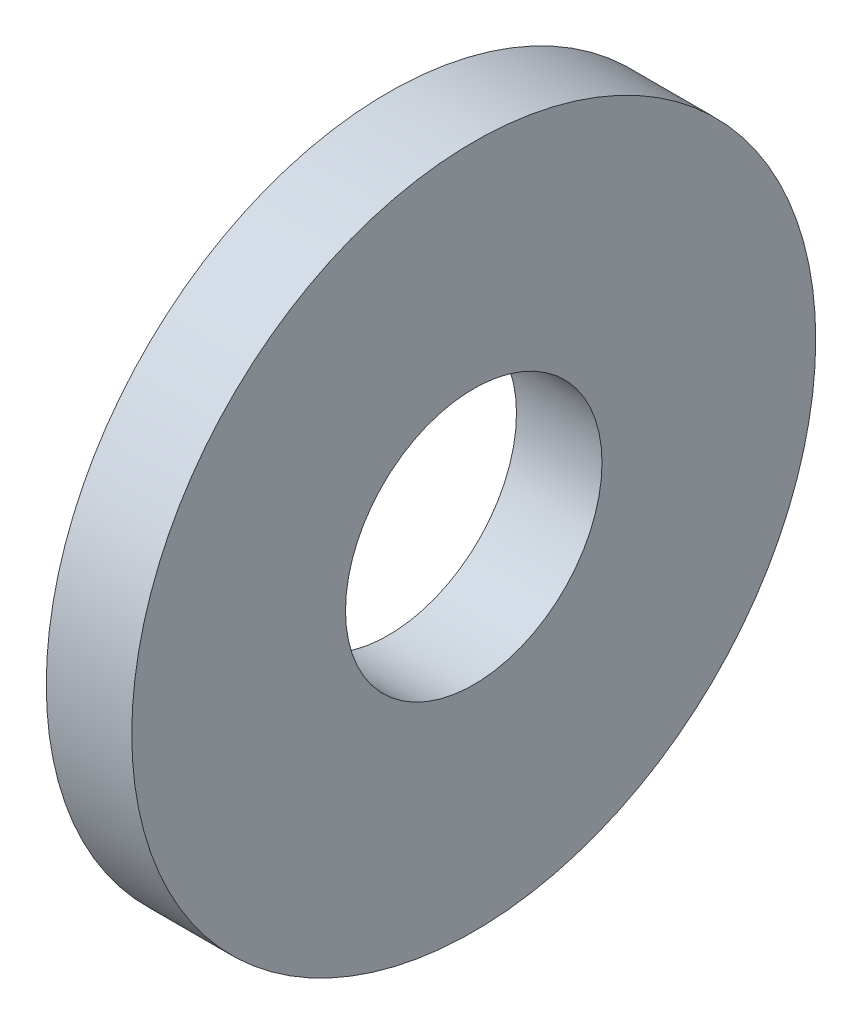
SolidWorks part; units mm, degrees
ref_plane "Front Plane" through (0, 0, 0) normal (0, 0, 1) x (1, 0, 0)
ref_plane "Top Plane" through (0, 0, 0) normal (0, 1, 0) x (1, 0, 0)
ref_plane "Right Plane" through (0, 0, 0) normal (1, 0, 0) x (0, 0, -1)
sketch "Sketch1" plane through (0, 0, 0) normal (0, 0, 1) x (1, 0, 0)
  line L0 (0, 0) -> (2.8605, 0) construction
  line L1 (-0.5, 4) -> (0.5, 4)
  line L2 (-0.5, 4) -> (-0.5, 1.5)
  line L3 (-0.5, 1.5) -> (0.5, 1.5)
  line L4 (0.5, 4) -> (0.5, 1.5)
  point P5 (0, 1.5)
  dimension "D1" = 1.5
  dimension "D2" = 4
  dimension "D3" = 1
revolve "Revolve1" add sketch "Sketch1" angle 360 about L0
